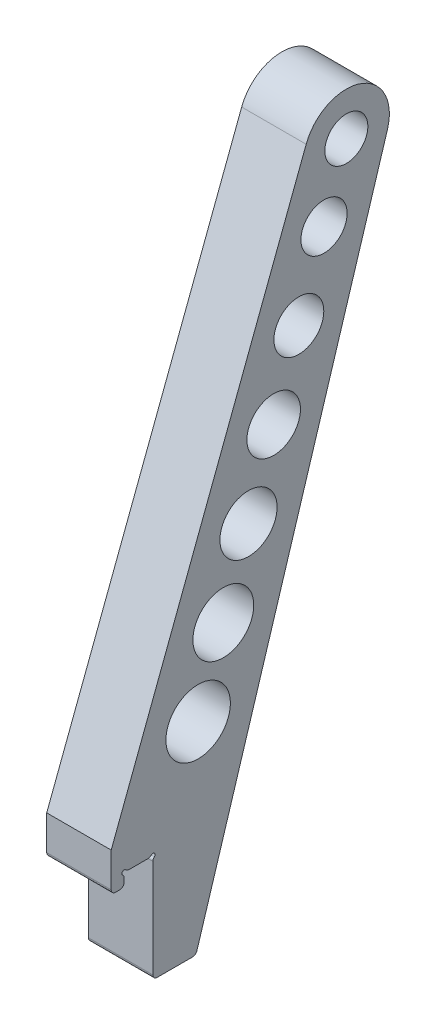
SolidWorks part; units mm, degrees
ref_plane "Front Plane" through (0, 0, 0) normal (0, 0, 1) x (1, 0, 0)
ref_plane "Top Plane" through (0, 0, 0) normal (0, 1, 0) x (1, 0, 0)
ref_plane "Right Plane" through (0, 0, 0) normal (1, 0, 0) x (0, 0, -1)
sketch "Sketch2" plane through (0, 0, 0) normal (1, 0, 0) x (0, 0, -1)
  line L0 (0, 0) -> (-6.7, 0)
  line L1 (-6.7, 0) -> (-6.7, -3)
  line L2 (0, 0) -> (0, -25)
  line L3 (-6.7, -3) -> (-9.7, -3)
  line L4 (-9.7, -3) -> (-9.7, 6)
  line L5 (-9.7, 6) -> (10, 6) construction
  line L6 (10, 6) -> (10, -25) construction
  line L7 (0, -25) -> (10, -25)
  line L9 (-6.2, -5) -> (-6.2, 0) construction
  line L10 (-6.2, -40) -> (0, -40) construction
  line L11 (-9.7, 6) -> (35.6505, 125.5109)
  line L12 (10, -25) -> (54.5532, 119.0075)
  line L13 (45, 121.9631) -> (10.5253, 21.7595) construction
  line L14 (-2.0748, 26.0945) -> (23.1254, 17.4245) construction
  line L15 (17.6729, 19.4875) -> (49.7651, 120.4485) construction
  circle A0 centre (45, 121.9631) radius 5
  arc A1 (35.6505, 125.5109) -> (54.5532, 119.0075) centre (45, 121.9631) cw
  circle A2 centre (10.5253, 21.7595) radius 7.5
  circle A3 centre (16.3812, 38.7803) radius 7.0753
  circle A4 centre (22.2372, 55.8011) radius 6.6507
  circle A5 centre (28.0931, 72.8219) radius 6.226
  circle A6 centre (33.9491, 89.8427) radius 5.8014
  circle A7 centre (39.805, 106.8635) radius 5.3767
  point P37 (0, 0)
  dimension "D8" = 10
  dimension "D10" = 10
  dimension "D12" = 15
  dimension "D1" = 0.5
  dimension "D2" = 3
  dimension "D3" = 6
  dimension "D4" = 3
  dimension "D5" = 15
  dimension "D6" = 10
  dimension "D7" = 130
  dimension "D9" = 45
  dimension "D11" = 24
  dimension "D13" = 18
  dimension "D14" = 18
  dimension "D15" = 18
  dimension "D16" = 18
  dimension "D17" = 18
extrude "Boss-Extrude1" add sketch "Sketch2" along normal blind 15
sketch "Sketch3" plane through (0, 0, 0) normal (1, 0, 0) x (0, 0, -1)
  circle A0 centre (0, 0) radius 0.5
  circle A1 centre (-6.7, 0) radius 0.5
  dimension "D1" = 1
extrude "Cut-Extrude2" cut sketch "Sketch3" along normal through all
fillet "Fillet1" radius 1 6 edges at (7.5, -0.5, 6.7) (7.5, 0, 6.2) (7.5, 0, 0.5) (7.5, -0.5, 0) (7.5, -3, 9.7) (7.5, -3, 6.7)
fillet "Fillet3" radius 1 2 edges at (7.5, -25, 0) (7.5, -25, -10)
sketch "Sketch4" plane through (0, -25, 0) normal (0, -1, 0) x (1, 0, 0)
  line L0 (7.5, 0) -> (7.5, -5) construction
  line L2 (0, 0) -> (15, 0) construction
  line L4 (-70, 0) -> (300, 0) construction
  circle A0 centre (7.5, -5) radius 2
  point P2 (16, 0)
  point P3 (0, 0)
  dimension "D1" = 4
  dimension "D2" = 5
extrude "Cut-Extrude3" cut sketch "Sketch4" against normal blind 9
equation "\"D14@Sketch2\"=\"D13@Sketch2\""
equation "\"D15@Sketch2\"=\"D13@Sketch2\""
equation "\"D16@Sketch2\"=\"D13@Sketch2\""
equation "\"D17@Sketch2\"=\"D13@Sketch2\""
